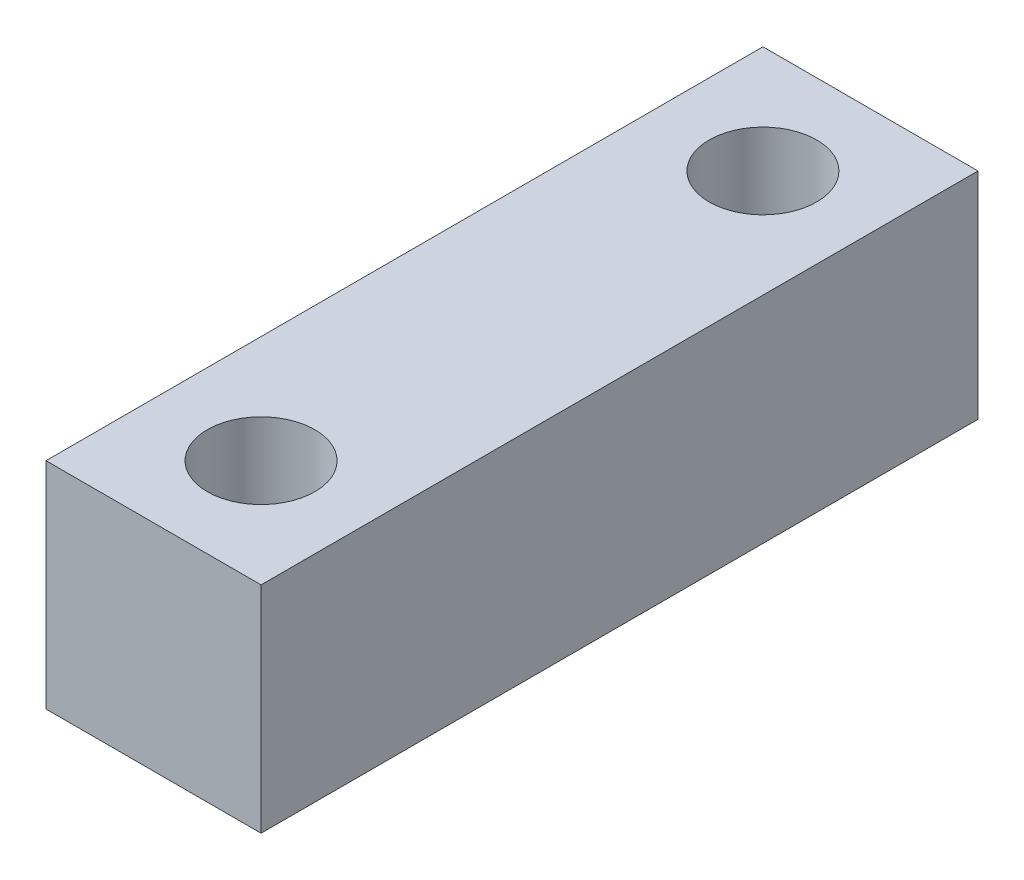
SolidWorks part; units mm, degrees
ref_plane "Front Plane" through (0, 0, 0) normal (0, 0, 1) x (1, 0, 0)
ref_plane "Top Plane" through (0, 0, 0) normal (0, 1, 0) x (1, 0, 0)
ref_plane "Right Plane" through (0, 0, 0) normal (1, 0, 0) x (0, 0, -1)
sketch "Sketch1" plane through (0, 0, 0) normal (0, 0, 1) x (1, 0, 0)
  line L1 (-15, -15) -> (15, -15)
  line L2 (-15, -15) -> (-15, 15)
  line L3 (-15, 15) -> (15, 15)
  line L4 (15, -15) -> (15, 15)
  line L5 (-15, -15) -> (15, 15) construction
  line L6 (-15, 15) -> (15, -15) construction
  point P0 (0, 0)
  dimension "D1" = 30
  dimension "D2" = 30
extrude "Boss-Extrude1" add sketch "Sketch1" along normal blind 100
sketch "Sketch2" plane through (0, 15, 0) normal (0, 1, 0) x (1, 0, 0)
  line L0 (0, 0) -> (0, -100) construction
  line L1 (15, -100) -> (-15, -100) construction
  line L2 (15, 0) -> (-15, 0) construction
  circle A0 centre (0, -15) radius 7.5
  circle A1 centre (0, -85) radius 7.5
  dimension "D1" = 15
  dimension "D2" = 15
  dimension "D3" = 15
  dimension "D4" = 15
extrude "Cut-Extrude1" cut sketch "Sketch2" against normal blind 100
